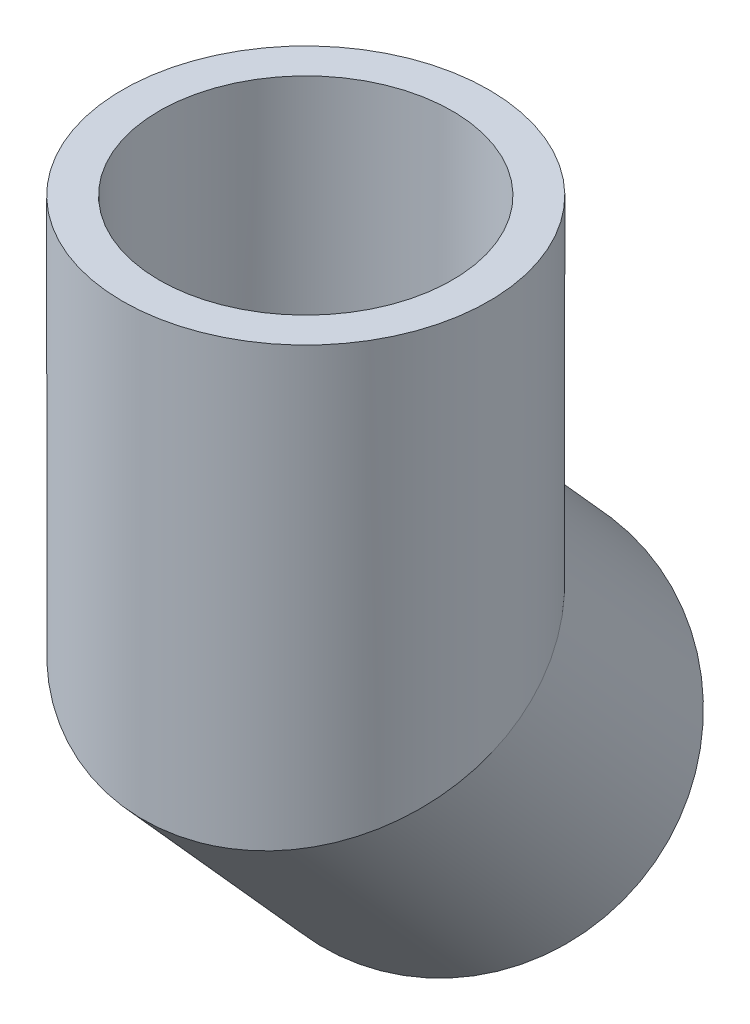
SolidWorks part; units mm, degrees
ref_plane "前视基准面" through (0, 0, 0) normal (0, 0, 1) x (1, 0, 0)
ref_plane "上视基准面" through (0, 0, 0) normal (0, 1, 0) x (1, 0, 0)
ref_plane "右视基准面" through (0, 0, 0) normal (1, 0, 0) x (0, 0, -1)
sketch3d "3D草图1"
  line L0 (0, 0, 0) -> (0, -25, 0)
  line L1 (0, -25, 0) -> (-6.306, -42.6777, -16.5147)
  dimension "D1" = 135
  dimension "D2" = 25
sketch "草图2" plane through (0, 0, 0) normal (0, 1, 0) x (1, 0, 0)
  circle A0 centre (0, 0) radius 12.5
  circle A1 centre (0, 0) radius 10
  dimension "D1" = 25
  dimension "D2" = 20
sweep "扫描1" add profiles "草图2" path "3D草图1"
